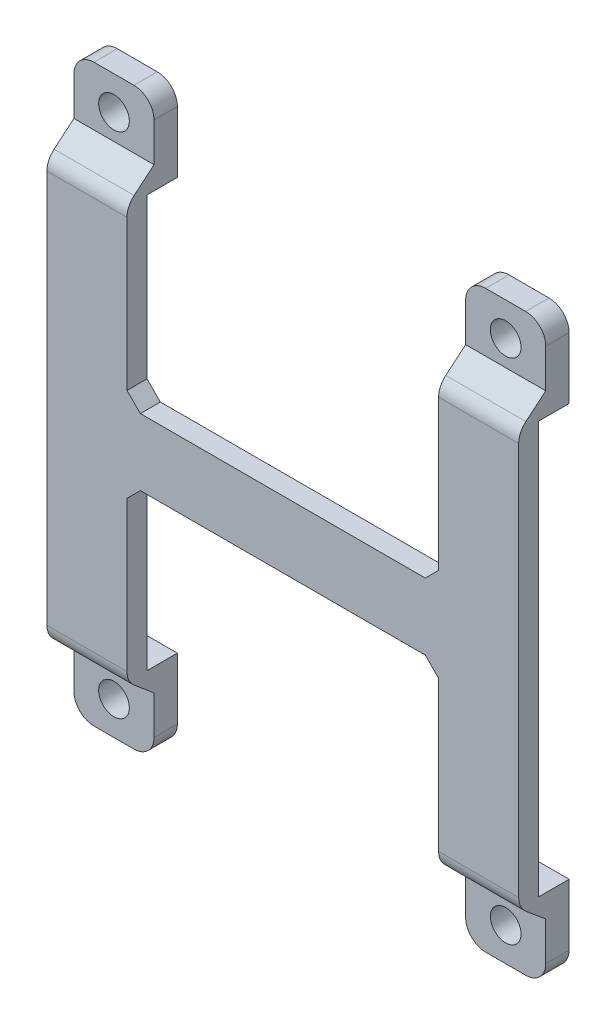
SolidWorks part; units mm, degrees
ref_plane "Front Plane" through (0, 0, 0) normal (0, 0, 1) x (1, 0, 0)
ref_plane "Top Plane" through (0, 0, 0) normal (0, 1, 0) x (1, 0, 0)
ref_plane "Right Plane" through (0, 0, 0) normal (1, 0, 0) x (0, 0, -1)
sketch "Sketch1" plane through (0, 0, 0) normal (0, 0, 1) x (1, 0, 0)
  line L0 (-44.8726, 37.3715) -> (-32.8726, 37.3715)
  line L1 (-44.8726, 37.3715) -> (-44.8726, 27.3715)
  line L2 (-44.8726, 27.3715) -> (-32.8726, 27.3715)
  line L3 (-32.8726, 37.3715) -> (-32.8726, 27.3715)
  line L4 (-44.8726, 37.3715) -> (-32.8726, 27.3715) construction
  line L5 (-44.8726, 27.3715) -> (-32.8726, 37.3715) construction
  line L6 (13.8274, 37.3715) -> (25.8274, 37.3715)
  line L7 (13.8274, 37.3715) -> (13.8274, 27.3715)
  line L8 (13.8274, 27.3715) -> (25.8274, 27.3715)
  line L9 (25.8274, 37.3715) -> (25.8274, 27.3715)
  line L10 (13.8274, 37.3715) -> (25.8274, 27.3715) construction
  line L11 (13.8274, 27.3715) -> (25.8274, 37.3715) construction
  line L12 (-44.8726, -38.7785) -> (-32.8726, -38.7785)
  line L13 (-44.8726, -38.7785) -> (-44.8726, -48.7785)
  line L14 (-44.8726, -48.7785) -> (-32.8726, -48.7785)
  line L15 (-32.8726, -38.7785) -> (-32.8726, -48.7785)
  line L16 (-44.8726, -38.7785) -> (-32.8726, -48.7785) construction
  line L17 (-44.8726, -48.7785) -> (-32.8726, -38.7785) construction
  line L18 (13.8274, -38.7785) -> (25.8274, -38.7785)
  line L19 (13.8274, -38.7785) -> (13.8274, -48.7785)
  line L20 (13.8274, -48.7785) -> (25.8274, -48.7785)
  line L21 (25.8274, -38.7785) -> (25.8274, -48.7785)
  line L22 (13.8274, -38.7785) -> (25.8274, -48.7785) construction
  line L23 (13.8274, -48.7785) -> (25.8274, -38.7785) construction
  line L24 (-44.8726, 27.3715) -> (-44.8726, -38.7785)
  line L25 (-32.8726, -38.7785) -> (-32.8726, 27.3715)
  line L26 (13.8274, 27.3715) -> (13.8274, -38.7785)
  line L27 (25.8274, 27.3715) -> (25.8274, -38.7785)
  line L28 (-32.8726, -5.7035) -> (13.8274, -5.7035) construction
  line L29 (-44.8726, -0.7035) -> (25.8274, -0.7035)
  line L30 (-44.8726, -0.7035) -> (-44.8726, -10.7035)
  line L31 (-44.8726, -10.7035) -> (25.8274, -10.7035)
  line L32 (25.8274, -0.7035) -> (25.8274, -10.7035)
  line L33 (-44.8726, -0.7035) -> (25.8274, -10.7035) construction
  line L34 (-44.8726, -10.7035) -> (25.8274, -0.7035) construction
  circle A0 centre (-38.8726, 32.3715) radius 2.3
  circle A1 centre (19.8274, 32.3715) radius 2.3
  circle A2 centre (-38.8726, -43.7785) radius 2.3
  circle A3 centre (19.8274, -43.7785) radius 2.3
  circle A4 centre (-38.8726, 32.3715) radius 2.8702 construction
  circle A5 centre (19.8274, 32.3715) radius 2.8702 construction
  circle A6 centre (-38.8726, -43.7785) radius 2.8702 construction
  circle A7 centre (19.8274, -43.7785) radius 2.8702 construction
  point P26 (-9.5226, -5.7035)
  point P31 (0, 0)
  dimension "D1" = 4.6
  dimension "D2" = 12
  dimension "D3" = 10
  dimension "D4" = 10
extrude "Boss-Extrude1" add sketch "Sketch1" along normal blind 3 and the other way blind 4.55 contours L3 L0 L1 L2 A0 | L24 L29 L25 L2 | L24 L31 L25 L29 | L31 L24 L12 L25 | L15 L12 L13 L14 A2 | L31 L26 L18 L27 | L21 L18 L19 L20 A3 | L26 L31 L27 L29 | L25 L31 L26 L29 | L26 L29 L27 L8 | L9 L6 L7 L8 A1
sketch "Sketch5" plane through (0, 0, -4.55) normal (0, 0, -1) x (-1, 0, 0)
  line L0 (-25.8274, 37.3715) -> (-25.8274, -48.7785) construction
  line L1 (-25.8274, 25.1715) -> (-13.8274, 25.1715)
  line L2 (-25.8274, 25.1715) -> (-25.8274, -36.5695)
  line L3 (-25.8274, -36.5695) -> (-13.8274, -36.5695)
  line L4 (-13.8274, 25.1715) -> (-13.8274, -36.5695)
  line L5 (32.8726, 25.1715) -> (44.8726, 25.1715)
  line L6 (32.8726, 25.1715) -> (32.8726, -36.5695)
  line L7 (32.8726, -36.5695) -> (44.8726, -36.5695)
  line L8 (44.8726, 25.1715) -> (44.8726, -36.5695)
  line L9 (-25.8274, -0.7035) -> (44.8726, -0.7035)
  line L10 (-25.8274, -0.7035) -> (-25.8274, -10.7035)
  line L11 (-25.8274, -10.7035) -> (44.8726, -10.7035)
  line L12 (44.8726, -0.7035) -> (44.8726, -10.7035)
  line L13 (-31.8234, 25.1715) -> (50.8726, 25.1715) construction
  line L14 (32.8726, 37.3715) -> (32.8726, -0.7035) construction
  line L15 (-13.8274, -10.7035) -> (-13.8274, -48.7785) construction
  line L16 (-25.8274, 37.3715) -> (-25.8274, -48.7785) construction
  line L17 (-26.1321, -36.5695) -> (-31.8234, -36.5695) construction
  line L18 (44.8726, 37.3715) -> (44.8726, -48.7785) construction
  line L19 (50.8726, -36.5695) -> (45.1812, -36.5695) construction
  point P10 (0, 0)
  point P18 (-29.8274, 25.1715)
  point P23 (28.8726, 25.1715)
  point P26 (-29.8274, -36.5696)
  point P27 (-29.8274, -36.8324)
  point P28 (-29.8274, -36.4747)
  point P29 (-29.8274, -38.1305)
  point P31 (0, 0)
  point P32 (-29.8274, -36.5746)
  point P34 (-29.8274, -36.5695)
  point P37 (-10.3889, -36.3695)
  point P38 (48.8726, -36.8279)
  point P41 (48.8726, -36.5695)
  line M2 (32.8726, 37.3715) -> (32.8726, -0.7035)
  line M3 (32.8726, -0.7035) -> (-13.8274, -0.7035)
  line M4 (-13.8274, -0.7035) -> (-13.8274, 37.3715)
  line M6 (-25.8274, 37.3715) -> (-25.8274, -48.7785)
  line M8 (-13.8274, -48.7785) -> (-13.8274, -10.7035)
  line M9 (-13.8274, -10.7035) -> (32.8726, -10.7035)
  line M10 (32.8726, -10.7035) -> (32.8726, -48.7785)
  line M12 (44.8726, -48.7785) -> (44.8726, 37.3715)
extrude "Cut-Extrude1" cut sketch "Sketch5" against normal blind 4.55 contours L9 L1 M6 M4 | L2 L11 L4 L9 | L11 L3 M6 M8 | L6 L4 M3 M9 | L6 L11 L8 L9 | L11 L7 M10 M12 | L9 L8 L5 M2
sketch "Sketch6" plane through (-44.8726, 0, 0) normal (-1, 0, 0) x (0, 0, 1)
  line L0 (3, 25.1715) -> (-1.05, 28.5698)
  line L1 (3, 37.3715) -> (3, -48.7785) construction
  line L2 (0, -36.5785) -> (3, -36.5785) construction
  line L3 (0, 25.1715) -> (3, 25.1715) construction
  line L4 (-1.05, 25.1715) -> (-1.05, 37.3715)
  line L5 (0, 25.1715) -> (-4.55, 25.1715) construction
  line L6 (-4.55, 37.3715) -> (3, 37.3715) construction
  line L7 (-4.55, 37.3715) -> (-4.55, 25.1715) construction
  line L8 (-1.05, 37.3715) -> (3, 37.3715)
  line L9 (3, 37.3715) -> (3, 25.1715)
  line L10 (3, -5.7035) -> (0, -5.7035) construction
  line L12 (3, -48.7785) -> (3, -36.5785)
  line L13 (-1.05, -48.7785) -> (3, -48.7785)
  line L14 (-1.05, -36.5785) -> (-1.05, -48.7785)
  line L15 (3, -36.5785) -> (-1.05, -39.9769)
  point P26 (2.8708, -48.7662)
  dimension "D1" = 3.5
  dimension "D2" = 50
extrude "Cut-Extrude2" cut sketch "Sketch6" against normal through all
chamfer "Chamfer1" distance 2 angle 45 4 edges at (-32.8726, -10.7035, 1.5) (-32.8726, -0.7035, 1.5) (13.8274, -10.7035, 1.5) (13.8274, -0.7035, 1.5)
fillet "Fillet1" radius 3 8 edges at (25.8274, -48.7785, -2.8) (13.8274, -48.7785, -2.8) (-32.8726, -48.7785, -2.8) (-44.8726, -48.7785, -2.8) (25.8274, 37.3715, -2.8) (13.8274, 37.3715, -2.8) (-32.8726, 37.3715, -2.8) (-44.8726, 37.3715, -2.8)
fillet "Fillet2" radius 3 4 edges at (19.8274, -36.5785, 3) (-38.8726, -36.5785, 3) (19.8274, 25.1715, 3) (-38.8726, 25.1715, 3)
equation "\"D2@Boss-Extrude1\"=4.55"
